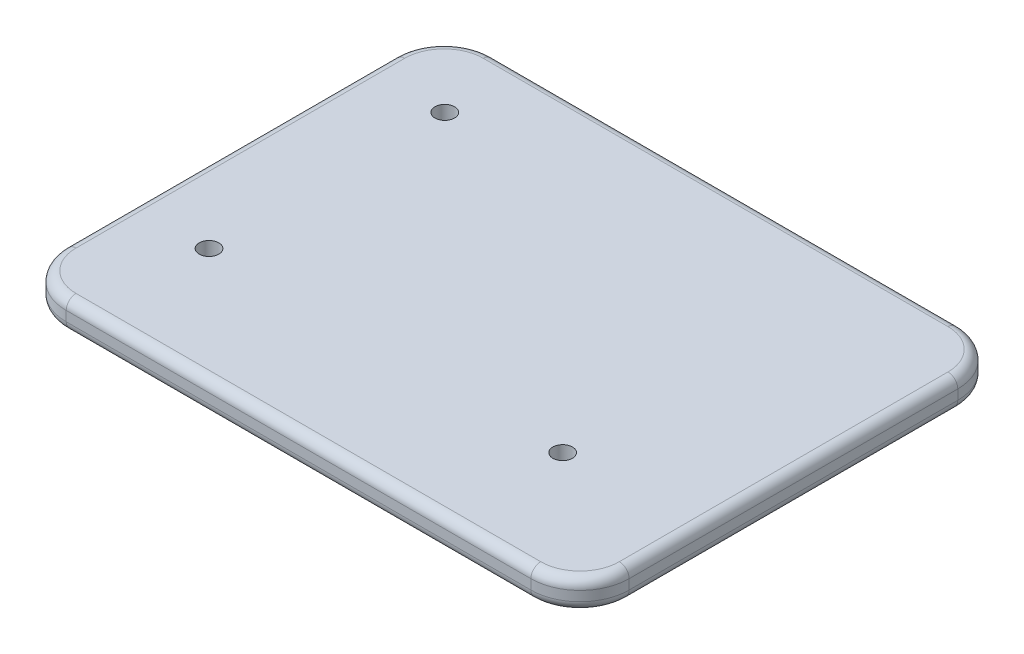
SolidWorks part; units mm, degrees
ref_plane "Front Plane" through (0, 0, 0) normal (0, 0, 1) x (1, 0, 0)
ref_plane "Top Plane" through (0, 0, 0) normal (0, 1, 0) x (1, 0, 0)
ref_plane "Right Plane" through (0, 0, 0) normal (1, 0, 0) x (0, 0, -1)
sketch "Sketch1" plane through (0, 0, 0) normal (0, 1, 0) x (-1, 0, 0)
  line L8 (-31.655, 18.23) -> (-31.655, -15.23)
  line L9 (-26.655, -20.23) -> (20.655, -20.23)
  line L10 (25.655, -15.23) -> (25.655, 18.23)
  line L11 (20.655, 23.23) -> (-26.655, 23.23)
  circle A0 centre (-18.155, 11.5) radius 1
  circle A1 centre (17.845, 11.5) radius 1
  circle A2 centre (17.845, -12.5) radius 1
  arc A8 (-31.655, -15.23) -> (-26.655, -20.23) centre (-26.655, -15.23) ccw
  arc A9 (20.655, -20.23) -> (25.655, -15.23) centre (20.655, -15.23) ccw
  arc A10 (25.655, 18.23) -> (20.655, 23.23) centre (20.655, 18.23) ccw
  arc A11 (-26.655, 23.23) -> (-31.655, 18.23) centre (-26.655, 18.23) ccw
extrude "Boss-Extrude1" add sketch "Sketch1" along normal blind 3
fillet "Fillet1" radius 1 16 edges at (-24.1905, 3, -18.7655) (3, 3, -20.23) (30.1905, 3, -18.7655) (31.655, 3, 1.5) (30.1905, 3, 21.7655) (3, 3, 23.23) (-24.1905, 3, 21.7655) (-25.655, 3, 1.5) (-24.1905, 0, -18.7655) (3, 0, -20.23) (30.1905, 0, -18.7655) (31.655, 0, 1.5) (30.1905, 0, 21.7655) (3, 0, 23.23) (-24.1905, 0, 21.7655) (-25.655, 0, 1.5)
